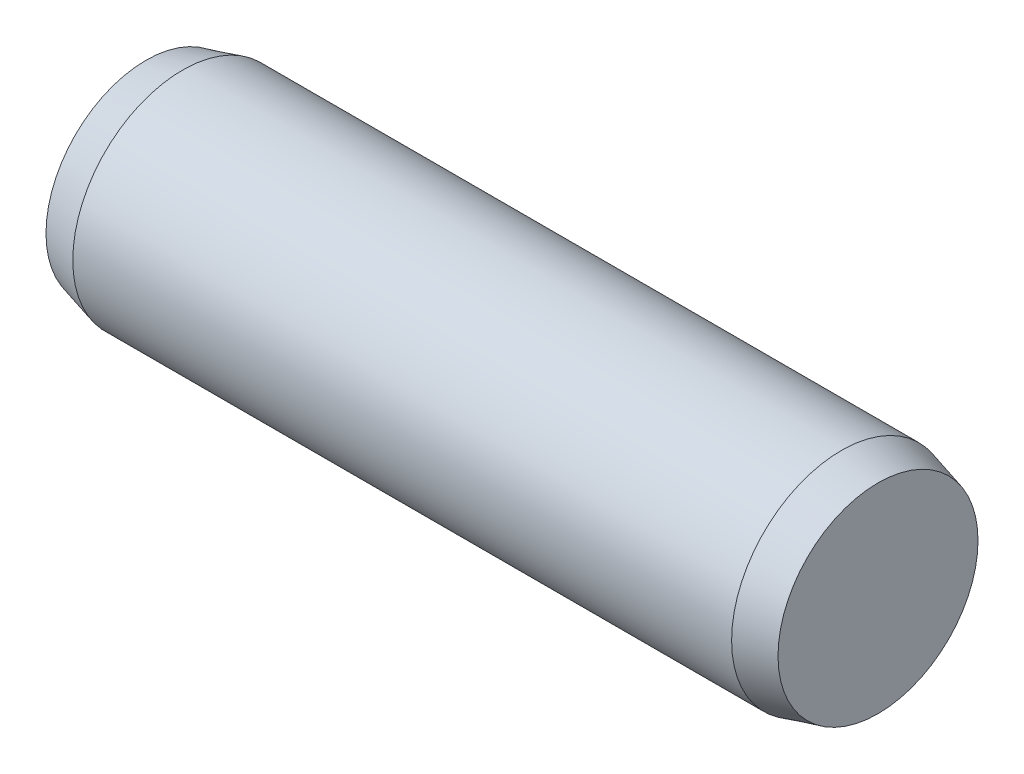
SolidWorks part; units mm, degrees
ref_plane "Plane1" through (0, 0, 0) normal (0, 0, 1) x (1, 0, 0)
ref_plane "Plane2" through (0, 0, 0) normal (0, 1, 0) x (1, 0, 0)
ref_plane "Plane3" through (0, 0, 0) normal (1, 0, 0) x (0, 0, -1)
sketch "Sketch1" plane through (0, 0, 0) normal (0, 0, 1) x (1, 0, 0)
  line L1 (-6.35, 0) -> (107.95, 0) construction
  line L2 (0, 0) -> (10, 0)
  line L3 (10, 0) -> (10, 1.366)
  line L4 (10, 1.366) -> (9.5, 1.5)
  line L5 (9.5, 1.5) -> (0.5, 1.5)
  line L6 (0, 1.366) -> (0, 0)
  line L7 (0, 1.366) -> (0.5, 1.5)
  dimension "Chamfer_len" = 0.5
  dimension "D3" = 15
  dimension "Diameter" = 3
  dimension "D1" = 0.5
  dimension "D2" = 15
  dimension "Length" = 10
revolve "Base-Revolve" add sketch "Sketch1" angle 360 about L1
equation "\"D3@Sketch1\" = 15.0"
equation "\"D1@Sketch1\" = \"Chamfer_len@Sketch1\""
equation "\"D2@Sketch1\" = \"D3@Sketch1\""
